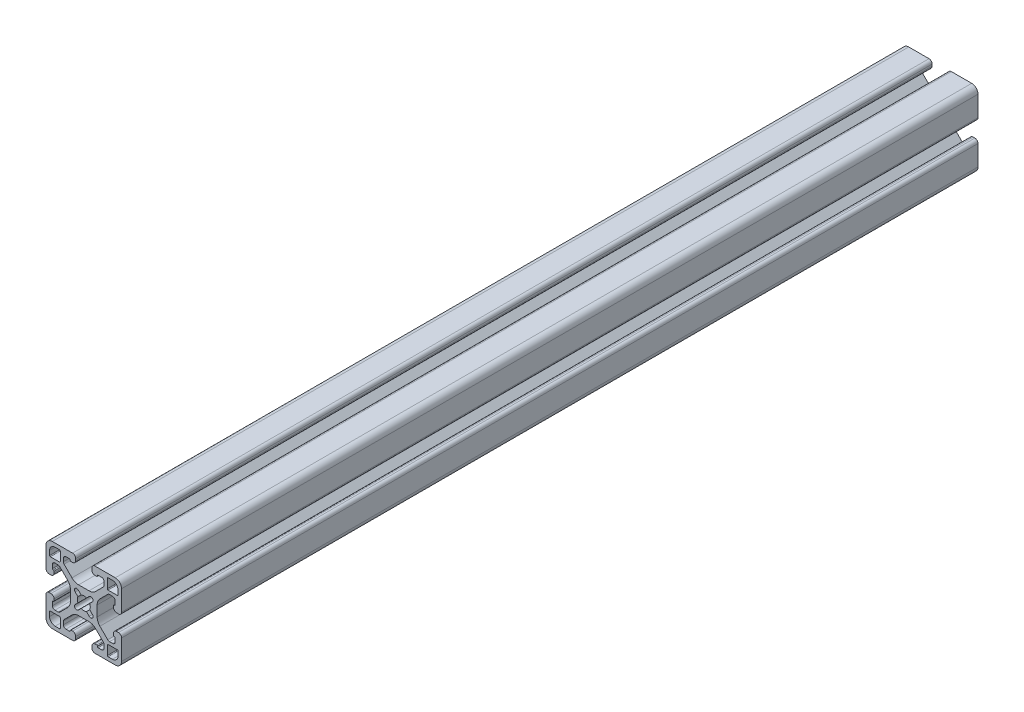
SolidWorks part; units mm, degrees
ref_plane "Front Plane" through (0, 0, 0) normal (0, 0, 1) x (1, 0, 0)
ref_plane "Top Plane" through (0, 0, 0) normal (0, 1, 0) x (1, 0, 0)
ref_plane "Right Plane" through (0, 0, 0) normal (1, 0, 0) x (0, 0, -1)
sketch "Sketch1" plane through (0, 0, 0) normal (0, 0, 1) x (1, 0, 0)
  line L0 (-66.7042, -2.4885) -> (-65.3338, -1.1181)
  line L1 (-65.3338, 1.5948) -> (-66.7042, 2.9652)
  line L2 (-65.0878, 4.5817) -> (-63.7174, 3.2113)
  line L3 (-61.0045, 3.2113) -> (-59.7212, 4.484)
  line L4 (-58.1153, 2.8781) -> (-59.3881, 1.5948)
  line L5 (-59.3881, -1.1181) -> (-58.0176, -2.4885)
  line L6 (-59.6341, -4.1049) -> (-61.0045, -2.7345)
  line L7 (-63.7174, -2.7345) -> (-65.0878, -4.1049)
  line L8 (-79.6075, 12.4812) -> (-79.6075, 14.691)
  line L9 (-76.8135, 17.485) -> (-74.6037, 17.485)
  line L10 (-74.2227, 17.104) -> (-74.2227, 12.4812)
  line L11 (-74.6037, 12.1002) -> (-79.2265, 12.1002)
  line L12 (-74.6037, -17.0082) -> (-76.8135, -17.0082)
  line L13 (-79.6075, -14.2142) -> (-79.6075, -12.0044)
  line L14 (-79.2265, -11.6234) -> (-74.6037, -11.6234)
  line L15 (-74.2227, -12.0044) -> (-74.2227, -16.6272)
  line L16 (-45.1143, -12.0044) -> (-45.1143, -14.2142)
  line L17 (-47.9083, -17.0082) -> (-50.1181, -17.0082)
  line L18 (-50.4991, -16.6272) -> (-50.4991, -12.0044)
  line L19 (-50.1181, -11.6234) -> (-45.4953, -11.6234)
  line L20 (-50.1181, 17.485) -> (-47.9083, 17.485)
  line L21 (-45.1143, 14.691) -> (-45.1143, 12.4812)
  line L22 (-45.4953, 12.1002) -> (-50.1181, 12.1002)
  line L23 (-50.4991, 12.4812) -> (-50.4991, 17.104)
  line L24 (-46.5368, -7.0006) -> (-46.5368, -8.7746)
  line L25 (-47.8067, -10.0486) -> (-49.3926, -10.0486)
  line L26 (-50.2907, -9.6767) -> (-54.2388, -5.7286)
  line L27 (-55.6299, -2.3699) -> (-55.6299, 2.8467)
  line L28 (-54.2388, 6.2053) -> (-50.2907, 10.1534)
  line L29 (-49.3926, 10.5254) -> (-47.8067, 10.5254)
  line L30 (-46.5368, 9.2513) -> (-46.5368, 7.4774)
  line L31 (-46.9178, 7.0964) -> (-46.994, 7.0964)
  line L32 (-47.375, 6.7154) -> (-47.3749, 5.8772)
  line L33 (-45.8001, 4.3024) -> (-44.8857, 4.3024)
  line L34 (-43.3109, 5.8772) -> (-43.3109, 16.1134)
  line L35 (-46.4859, 19.2884) -> (-56.7221, 19.2884)
  line L36 (-58.2969, 17.7136) -> (-58.2969, 16.7992)
  line L37 (-56.7222, 15.2244) -> (-55.884, 15.2244)
  line L38 (-55.503, 15.6054) -> (-55.503, 15.6816)
  line L39 (-55.122, 16.0626) -> (-53.348, 16.0626)
  line L40 (-52.0739, 14.7926) -> (-52.0739, 13.2067)
  line L41 (-52.4459, 12.3087) -> (-56.394, 8.3606)
  line L42 (-59.7526, 6.9694) -> (-64.9693, 6.9694)
  line L43 (-68.3279, 8.3606) -> (-72.276, 12.3087)
  line L44 (-72.6479, 13.2067) -> (-72.6479, 14.7926)
  line L45 (-71.3739, 16.0626) -> (-69.5999, 16.0626)
  line L46 (-69.2189, 15.6816) -> (-69.2189, 15.6054)
  line L47 (-68.8379, 15.2244) -> (-67.9997, 15.2244)
  line L48 (-66.4249, 16.7992) -> (-66.4249, 17.7136)
  line L49 (-67.9997, 19.2884) -> (-78.2359, 19.2884)
  line L50 (-81.4109, 16.1134) -> (-81.4109, 5.8772)
  line L51 (-79.8361, 4.3024) -> (-78.9217, 4.3024)
  line L52 (-77.3469, 5.8772) -> (-77.3469, 6.7154)
  line L53 (-77.7279, 7.0964) -> (-77.8041, 7.0964)
  line L54 (-78.1851, 7.4774) -> (-78.1851, 9.2513)
  line L55 (-76.9151, 10.5254) -> (-75.3293, 10.5254)
  line L56 (-74.4312, 10.1534) -> (-70.4831, 6.2053)
  line L57 (-69.0919, 2.8467) -> (-69.0919, -2.3699)
  line L58 (-70.4831, -5.7286) -> (-74.4312, -9.6767)
  line L59 (-75.3293, -10.0486) -> (-76.9151, -10.0486)
  line L60 (-78.1851, -8.7746) -> (-78.1851, -7.0006)
  line L61 (-77.8041, -6.6196) -> (-77.7279, -6.6196)
  line L62 (-77.3469, -6.2386) -> (-77.3469, -5.4004)
  line L63 (-78.9217, -3.8256) -> (-79.8361, -3.8256)
  line L64 (-81.4109, -5.4004) -> (-81.4109, -15.6366)
  line L65 (-78.2359, -18.8116) -> (-67.9997, -18.8116)
  line L66 (-66.4249, -17.2368) -> (-66.4249, -16.3224)
  line L67 (-67.9997, -14.7476) -> (-68.8379, -14.7476)
  line L68 (-69.2189, -15.1286) -> (-69.2189, -15.2048)
  line L69 (-69.5999, -15.5858) -> (-71.3739, -15.5858)
  line L70 (-72.6479, -14.3158) -> (-72.6479, -12.7299)
  line L71 (-72.276, -11.8319) -> (-68.3279, -7.8838)
  line L72 (-64.9693, -6.4926) -> (-59.7526, -6.4926)
  line L73 (-56.394, -7.8838) -> (-52.4459, -11.8319)
  line L74 (-52.0739, -12.7299) -> (-52.0739, -14.3158)
  line L75 (-53.348, -15.5858) -> (-55.122, -15.5858)
  line L76 (-55.503, -15.2048) -> (-55.503, -15.1286)
  line L77 (-55.884, -14.7476) -> (-56.7222, -14.7476)
  line L78 (-58.2969, -16.3224) -> (-58.2969, -17.2368)
  line L79 (-56.7221, -18.8116) -> (-46.4859, -18.8116)
  line L80 (-43.3109, -15.6366) -> (-43.3109, -5.4004)
  line L81 (-44.8857, -3.8256) -> (-45.8001, -3.8256)
  line L82 (-47.3749, -5.4004) -> (-47.375, -6.2386)
  line L83 (-46.994, -6.6196) -> (-46.9178, -6.6196)
  arc A0 (-66.7042, -2.4885) -> (-65.0878, -4.1049) centre (-65.896, -3.2967) ccw
  arc A1 (-65.3338, 1.5948) -> (-65.3338, -1.1181) centre (-62.3609, 0.2384) ccw
  arc A2 (-65.0878, 4.5817) -> (-66.7042, 2.9652) centre (-65.896, 3.7734) ccw
  arc A3 (-61.0045, 3.2113) -> (-63.7174, 3.2113) centre (-62.3609, 0.2384) ccw
  arc A4 (-58.1153, 2.8781) -> (-59.7212, 4.484) centre (-58.8259, 3.7734) ccw
  arc A5 (-59.3881, -1.1181) -> (-59.3881, 1.5948) centre (-62.3609, 0.2384) ccw
  arc A6 (-59.6341, -4.1049) -> (-58.0176, -2.4885) centre (-58.8259, -3.2967) ccw
  arc A7 (-63.7174, -2.7345) -> (-61.0045, -2.7345) centre (-62.3609, 0.2384) ccw
  arc A8 (-79.6075, 12.4812) -> (-79.2265, 12.1002) centre (-79.2265, 12.4812) ccw
  arc A9 (-76.8135, 17.485) -> (-79.6075, 14.691) centre (-76.8135, 14.691) ccw
  arc A10 (-74.2227, 17.104) -> (-74.6037, 17.485) centre (-74.6037, 17.104) ccw
  arc A11 (-74.6037, 12.1002) -> (-74.2227, 12.4812) centre (-74.6037, 12.4812) ccw
  arc A12 (-74.6037, -17.0082) -> (-74.2227, -16.6272) centre (-74.6037, -16.6272) ccw
  arc A13 (-79.6075, -14.2142) -> (-76.8135, -17.0082) centre (-76.8135, -14.2142) ccw
  arc A14 (-79.2265, -11.6234) -> (-79.6075, -12.0044) centre (-79.2265, -12.0044) ccw
  arc A15 (-74.2227, -12.0044) -> (-74.6037, -11.6234) centre (-74.6037, -12.0044) ccw
  arc A16 (-45.1143, -12.0044) -> (-45.4953, -11.6234) centre (-45.4953, -12.0044) ccw
  arc A17 (-47.9083, -17.0082) -> (-45.1143, -14.2142) centre (-47.9083, -14.2142) ccw
  arc A18 (-50.4991, -16.6272) -> (-50.1181, -17.0082) centre (-50.1181, -16.6272) ccw
  arc A19 (-50.1181, -11.6234) -> (-50.4991, -12.0044) centre (-50.1181, -12.0044) ccw
  arc A20 (-50.1181, 17.485) -> (-50.4991, 17.104) centre (-50.1181, 17.104) ccw
  arc A21 (-45.1143, 14.691) -> (-47.9083, 17.485) centre (-47.9083, 14.691) ccw
  arc A22 (-45.4953, 12.1002) -> (-45.1143, 12.4812) centre (-45.4953, 12.4812) ccw
  arc A23 (-50.4991, 12.4812) -> (-50.1181, 12.1002) centre (-50.1181, 12.4812) ccw
  arc A24 (-47.8067, -10.0486) -> (-46.5368, -8.7746) centre (-47.8067, -8.7786) ccw
  arc A25 (-50.2907, -9.6767) -> (-49.3926, -10.0486) centre (-49.3926, -8.7786) ccw
  arc A26 (-55.6299, -2.3699) -> (-54.2388, -5.7286) centre (-50.8801, -2.3699) ccw
  arc A27 (-54.2388, 6.2053) -> (-55.6299, 2.8467) centre (-50.8801, 2.8467) ccw
  arc A28 (-49.3926, 10.5254) -> (-50.2907, 10.1534) centre (-49.3926, 9.2554) ccw
  arc A29 (-46.5368, 9.2513) -> (-47.8067, 10.5254) centre (-47.8067, 9.2554) ccw
  arc A30 (-46.9178, 7.0964) -> (-46.5368, 7.4774) centre (-46.9178, 7.4774) ccw
  arc A31 (-46.994, 7.0964) -> (-47.375, 6.7154) centre (-46.994, 6.7154) ccw
  arc A32 (-47.3749, 5.8772) -> (-45.8001, 4.3024) centre (-45.8001, 5.8772) ccw
  arc A33 (-44.8857, 4.3024) -> (-43.3109, 5.8772) centre (-44.8857, 5.8772) ccw
  arc A34 (-43.3109, 16.1134) -> (-46.4859, 19.2884) centre (-46.4859, 16.1134) ccw
  arc A35 (-56.7221, 19.2884) -> (-58.2969, 17.7136) centre (-56.7221, 17.7136) ccw
  arc A36 (-58.2969, 16.7992) -> (-56.7222, 15.2244) centre (-56.7221, 16.7992) ccw
  arc A37 (-55.884, 15.2244) -> (-55.503, 15.6054) centre (-55.884, 15.6054) ccw
  arc A38 (-55.122, 16.0626) -> (-55.503, 15.6816) centre (-55.122, 15.6816) ccw
  arc A39 (-52.0739, 14.7926) -> (-53.348, 16.0626) centre (-53.3439, 14.7926) ccw
  arc A40 (-52.4459, 12.3087) -> (-52.0739, 13.2067) centre (-53.3439, 13.2067) ccw
  arc A41 (-59.7526, 6.9694) -> (-56.394, 8.3606) centre (-59.7526, 11.7192) ccw
  arc A42 (-68.3279, 8.3606) -> (-64.9693, 6.9694) centre (-64.9693, 11.7192) ccw
  arc A43 (-72.6479, 13.2067) -> (-72.276, 12.3087) centre (-71.3779, 13.2067) ccw
  arc A44 (-71.3739, 16.0626) -> (-72.6479, 14.7926) centre (-71.3779, 14.7926) ccw
  arc A45 (-69.2189, 15.6816) -> (-69.5999, 16.0626) centre (-69.5999, 15.6816) ccw
  arc A46 (-69.2189, 15.6054) -> (-68.8379, 15.2244) centre (-68.8379, 15.6054) ccw
  arc A47 (-67.9997, 15.2244) -> (-66.4249, 16.7992) centre (-67.9997, 16.7992) ccw
  arc A48 (-66.4249, 17.7136) -> (-67.9997, 19.2884) centre (-67.9997, 17.7136) ccw
  arc A49 (-78.2359, 19.2884) -> (-81.4109, 16.1134) centre (-78.2359, 16.1134) ccw
  arc A50 (-81.4109, 5.8772) -> (-79.8361, 4.3024) centre (-79.8361, 5.8772) ccw
  arc A51 (-78.9217, 4.3024) -> (-77.3469, 5.8772) centre (-78.9217, 5.8772) ccw
  arc A52 (-77.3469, 6.7154) -> (-77.7279, 7.0964) centre (-77.7279, 6.7154) ccw
  arc A53 (-78.1851, 7.4774) -> (-77.8041, 7.0964) centre (-77.8041, 7.4774) ccw
  arc A54 (-76.9151, 10.5254) -> (-78.1851, 9.2513) centre (-76.9151, 9.2554) ccw
  arc A55 (-74.4312, 10.1534) -> (-75.3293, 10.5254) centre (-75.3293, 9.2554) ccw
  arc A56 (-69.0919, 2.8467) -> (-70.4831, 6.2053) centre (-73.8417, 2.8467) ccw
  arc A57 (-70.4831, -5.7286) -> (-69.0919, -2.3699) centre (-73.8417, -2.3699) ccw
  arc A58 (-75.3293, -10.0486) -> (-74.4312, -9.6767) centre (-75.3293, -8.7786) ccw
  arc A59 (-78.1851, -8.7746) -> (-76.9151, -10.0486) centre (-76.9151, -8.7786) ccw
  arc A60 (-77.8041, -6.6196) -> (-78.1851, -7.0006) centre (-77.8041, -7.0006) ccw
  arc A61 (-77.7279, -6.6196) -> (-77.3469, -6.2386) centre (-77.7279, -6.2386) ccw
  arc A62 (-77.3469, -5.4004) -> (-78.9217, -3.8256) centre (-78.9217, -5.4004) ccw
  arc A63 (-79.8361, -3.8256) -> (-81.4109, -5.4004) centre (-79.8361, -5.4004) ccw
  arc A64 (-81.4109, -15.6366) -> (-78.2359, -18.8116) centre (-78.2359, -15.6366) ccw
  arc A65 (-67.9997, -18.8116) -> (-66.4249, -17.2368) centre (-67.9997, -17.2368) ccw
  arc A66 (-66.4249, -16.3224) -> (-67.9997, -14.7476) centre (-67.9997, -16.3224) ccw
  arc A67 (-68.8379, -14.7476) -> (-69.2189, -15.1286) centre (-68.8379, -15.1286) ccw
  arc A68 (-69.5999, -15.5858) -> (-69.2189, -15.2048) centre (-69.5999, -15.2048) ccw
  arc A69 (-72.6479, -14.3158) -> (-71.3739, -15.5858) centre (-71.3779, -14.3158) ccw
  arc A70 (-72.276, -11.8319) -> (-72.6479, -12.7299) centre (-71.3779, -12.7299) ccw
  arc A71 (-64.9693, -6.4926) -> (-68.3279, -7.8838) centre (-64.9693, -11.2424) ccw
  arc A72 (-56.394, -7.8838) -> (-59.7526, -6.4926) centre (-59.7526, -11.2424) ccw
  arc A73 (-52.0739, -12.7299) -> (-52.4459, -11.8319) centre (-53.3439, -12.7299) ccw
  arc A74 (-53.348, -15.5858) -> (-52.0739, -14.3158) centre (-53.3439, -14.3158) ccw
  arc A75 (-55.503, -15.2048) -> (-55.122, -15.5858) centre (-55.122, -15.2048) ccw
  arc A76 (-55.503, -15.1286) -> (-55.884, -14.7476) centre (-55.884, -15.1286) ccw
  arc A77 (-56.7222, -14.7476) -> (-58.2969, -16.3224) centre (-56.7221, -16.3224) ccw
  arc A78 (-58.2969, -17.2368) -> (-56.7221, -18.8116) centre (-56.7221, -17.2368) ccw
  arc A79 (-46.4859, -18.8116) -> (-43.3109, -15.6366) centre (-46.4859, -15.6366) ccw
  arc A80 (-43.3109, -5.4004) -> (-44.8857, -3.8256) centre (-44.8857, -5.4004) ccw
  arc A81 (-45.8001, -3.8256) -> (-47.3749, -5.4004) centre (-45.8001, -5.4004) ccw
  arc A82 (-47.375, -6.2386) -> (-46.994, -6.6196) centre (-46.994, -6.2386) ccw
  arc A83 (-46.5368, -7.0006) -> (-46.9178, -6.6196) centre (-46.9178, -7.0006) ccw
extrude "Extrude1" add sketch "Sketch1" against normal blind 431.8
